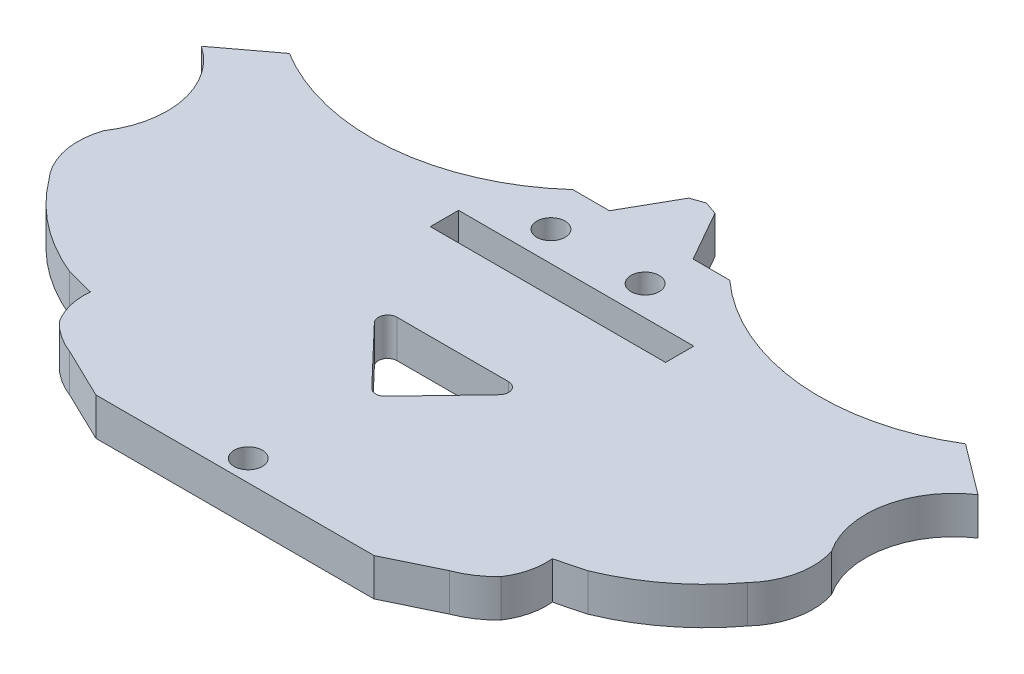
SolidWorks part; units mm, degrees
ref_plane "Front Plane" through (0, 0, 0) normal (0, 0, 1) x (1, 0, 0)
ref_plane "Top Plane" through (0, 0, 0) normal (0, 1, 0) x (1, 0, 0)
ref_plane "Right Plane" through (0, 0, 0) normal (1, 0, 0) x (0, 0, -1)
sketch "Sketch3" plane through (0, 0, 0) normal (0, 1, 0) x (1, 0, 0)
  line L0 (84.4541, 599.5572) -> (574.4541, 599.5572) construction
sketch "Sketch2" plane through (0, 0, 0) normal (0, 1, 0) x (1, 0, 0)
  line L0 (0, 0) -> (0, 57.603) construction
  line L1 (-18.1438, -7.9279) -> (18.1438, -7.9279) construction
  line L2 (-18.1438, -7.9279) -> (-18.1438, 7.9279) construction
  line L3 (-18.1438, 7.9279) -> (18.1438, 7.9279) construction
  line L4 (18.1438, -7.9279) -> (18.1438, 7.9279) construction
  line L5 (-18.1438, -7.9279) -> (18.1438, 7.9279) construction
  line L6 (-18.1438, 7.9279) -> (18.1438, -7.9279) construction
  line L7 (-21.8576, -11.143) -> (21.8576, -11.143) construction
  line L8 (-21.8576, -11.143) -> (-21.8576, 11.143) construction
  line L9 (-21.8576, 11.143) -> (21.8576, 11.143) construction
  line L10 (21.8576, -11.143) -> (21.8576, 11.143) construction
  line L11 (-21.8576, -11.143) -> (21.8576, 11.143) construction
  line L12 (-21.8576, 11.143) -> (21.8576, -11.143) construction
  line L13 (-8.5, 0) -> (8.5, 0) construction
  line L14 (0, 0) -> (0, -8.8619) construction
  line L15 (-20.6395, 7.1502) -> (-17.9674, 9.1598)
  line L16 (-4.1695, 10.4244) -> (4.1695, 10.4244)
  line L17 (-1.5343, -5.6375) -> (1.5343, -5.6375)
  line L18 (-10.0901, -10.3942) -> (-7.3916, -11.6987)
  line L19 (20.6395, 7.1502) -> (17.9674, 9.1598)
  line L20 (-2.2241, 10.4244) -> (-0.6961, 13.1148)
  line L21 (-0.6961, 13.1148) -> (0, 13.358)
  line L22 (2.2241, 10.4244) -> (0.6961, 13.1148)
  line L23 (0.6961, 13.1148) -> (0, 13.358)
  line L24 (-7.3916, -11.6987) -> (-0.7757, -11.143)
  line L25 (-0.7757, -11.143) -> (0, -10.9595)
  line L26 (0.7757, -11.143) -> (0, -10.9595)
  line L27 (7.3916, -11.6987) -> (0.7757, -11.143)
  line L28 (10.0901, -10.3942) -> (7.3916, -11.6987)
  line L29 (-16.4215, -5.191) -> (-11.7373, -9.2961)
  line L30 (16.4215, -5.191) -> (11.7373, -9.2961)
  line L31 (-7.3916, -11.6987) -> (7.3916, -11.6987)
  line L33 (-32.5, -20.0045) -> (32.5, -20.0045)
  line L34 (-32.5, -20.0045) -> (-32.5, 20.0045)
  line L35 (-32.5, 20.0045) -> (32.5, 20.0045)
  line L36 (32.5, -20.0045) -> (32.5, 20.0045)
  line L37 (-32.5, -20.0045) -> (32.5, 20.0045) construction
  line L38 (-32.5, 20.0045) -> (32.5, -20.0045) construction
  arc A0 (-4.1695, 10.4244) -> (-17.9674, 9.1598) centre (-11.9148, 19.0269) cw
  arc A1 (-20.6395, 7.1502) -> (-19.3461, 0.6629) centre (-23.2364, 3.2599) cw
  arc A2 (-19.3461, 0.6629) -> (-18.559, -3.0217) centre (-15.82, -0.5102) ccw
  arc A3 (-18.559, -3.0217) -> (-13.7831, -6.7121) centre (-9.4985, 3.7682) ccw
  arc A4 (-13.7831, -6.7121) -> (-6.6237, -7.9279) centre (-4.6259, 25.5245) ccw
  arc A5 (-1.5343, -5.6375) -> (-6.6237, -7.9279) centre (-1.5343, -12.4372) ccw
  arc A7 (13.7831, -6.7121) -> (6.6237, -7.9279) centre (4.6259, 25.5245) cw
  arc A8 (18.559, -3.0217) -> (13.7831, -6.7121) centre (9.4985, 3.7682) cw
  arc A9 (19.3461, 0.6629) -> (18.559, -3.0217) centre (15.82, -0.5102) cw
  arc A10 (20.6395, 7.1502) -> (19.3461, 0.6629) centre (23.2364, 3.2599) ccw
  arc A11 (4.1695, 10.4244) -> (17.9674, 9.1598) centre (11.9148, 19.0269) ccw
  arc A12 (1.5343, -5.6375) -> (6.6237, -7.9279) centre (1.5343, -12.4372) cw
  arc A14 (-12.2767, -7.1024) -> (-11.7373, -9.2961) centre (-8.8887, -7.4325) ccw
  arc A15 (-11.7373, -9.2961) -> (-10.0901, -10.3942) centre (-8.5052, -6.2323) ccw
  arc A16 (12.2767, -7.1024) -> (11.7373, -9.2961) centre (8.8887, -7.4325) cw
  arc A17 (11.7373, -9.2961) -> (10.0901, -10.3942) centre (8.5052, -6.2323) cw
  point P0 (0, 0)
  point P6 (0, 0)
  point P34 (0, 0)
  point P45 (0, 10.4244)
  point P54 (0, -5.6375)
  point P57 (-0.2087, -5.6375)
  point P72 (0, -11.6987)
  dimension "D2" = 65
  dimension "D1" = 17
extrude "Boss-Extrude1" add sketch "Sketch2" along normal blind 2
sketch "Sketch4" plane through (0, 0, 0) normal (0, 1, 0) x (1, 0, 0)
  line L0 (0, 0) -> (0, -15.9627) construction
  line L1 (0, 0) -> (0, 46.0631) construction
scale "Scale1" bodies to scale 101 scale about centroid uniform scaling yes scale factor 2
sketch "Sketch6" plane through (0, 3, 0) normal (0, 1, 0) x (1, 0, 0)
  line L0 (0, 0) -> (0, 27.4099) construction
  circle A0 centre (-5.8515, 16.2836) radius 1.5 construction
  circle A1 centre (-5.8515, 16.2836) radius 1.5
  circle A2 centre (4.1518, 16.2836) radius 1.5 construction
  circle A3 centre (4.1518, 16.2836) radius 1.5
extrude "Cut-Extrude2" cut sketch "Sketch6" against normal through all
sketch "Sketch7" plane through (0, 3, 0) normal (0, 1, 0) x (1, 0, 0)
  line L0 (0, 0) -> (0, 46.0631) construction
  line L1 (-12.5, 13.1109) -> (12.5, 13.1109)
  line L2 (-12.5, 13.1109) -> (-12.5, 10.1109)
  line L3 (-12.5, 10.1109) -> (12.5, 10.1109)
  line L4 (12.5, 13.1109) -> (12.5, 10.1109)
  line L5 (-12.5, 13.1109) -> (12.5, 10.1109) construction
  line L6 (-12.5, 10.1109) -> (12.5, 13.1109) construction
  point P0 (0, 11.6109)
  dimension "D1" = 3
  dimension "D2" = 25
extrude "Boss-Extrude2" add sketch "Sketch7" along normal blind 15
sketch "Sketch8" plane through (0, 0, -10.1109) normal (0, 0, 1) x (1, 0, 0)
  line L0 (0, 2.6097) -> (0, 7.1828) construction
  line L1 (-8, 16.4174) -> (8, 16.4174)
  line L2 (-8, 16.4174) -> (-8, 5.4174)
  line L3 (-8, 5.4174) -> (8, 5.4174)
  line L4 (8, 16.4174) -> (8, 5.4174)
  circle A0 centre (-9.75, 10.9174) radius 1.5
  circle A1 centre (9.75, 10.9174) radius 1.5
  point P4 (0, 5.4174)
  point P8 (-8, 10.9174)
  dimension "D3" = 3
  dimension "D4" = 1.75
  dimension "D1" = 16
  dimension "D2" = 11
extrude "Cut-Extrude3" cut sketch "Sketch8" against normal blind 18
fillet "Fillet3" radius 3 1 edges at (-12.5, 18, -11.6109)
fillet "Fillet4" radius 3 1 edges at (12.5, 18, -11.6109)
sketch "Sketch9" plane through (0, 3, 0) normal (0, 1, 0) x (1, 0, 0)
  line L21 (-7.6951, -21.8709) -> (-7.6951, -30.6829)
  line L22 (-7.6951, -30.6829) -> (5.9954, -30.6829)
  line L23 (5.9954, -30.6829) -> (5.9954, -21.8709)
  line L24 (5.9954, -21.8709) -> (8.9954, -21.8709)
  line L25 (8.9954, -21.8709) -> (8.9954, -30.0705)
  line L26 (8.9954, -30.0705) -> (18.6231, -24.4632)
  line L27 (18.6231, -24.4632) -> (23.9122, -21.0338)
  line L28 (25.28, -18.5167) -> (25.28, -3.348)
  line L29 (24.6327, -1.4865) -> (9.0527, 18.2043)
  line L30 (6.7, 19.3428) -> (3.3097, 19.3428)
  line L31 (3.3097, 19.3428) -> (0.5459, 24.5621)
  line L32 (0.5459, 24.5621) -> (-0.8499, 25.1844)
  line L33 (-0.8499, 25.1844) -> (-2.2456, 24.5621)
  line L34 (-2.2456, 24.5621) -> (-5.0094, 19.3428)
  line L35 (-5.0094, 19.3428) -> (-8.3997, 19.3428)
  line L36 (-10.7524, 18.2043) -> (-26.3324, -1.4865)
  line L37 (-26.9797, -3.348) -> (-26.9797, -18.5167)
  line L38 (-25.6119, -21.0338) -> (-20.3228, -24.4632)
  line L39 (-20.3228, -24.4632) -> (-10.6951, -30.0705)
  line L40 (-10.6951, -30.0705) -> (-10.6951, -21.8709)
  line L41 (-10.6951, -21.8709) -> (-7.6951, -21.8709)
  line L42 (-7.6951, -21.8709) -> (-7.6951, -30.6829)
  line L43 (-7.6951, -30.6829) -> (5.9954, -30.6829)
  line L44 (5.9954, -30.6829) -> (5.9954, -21.8709)
  line L45 (5.9954, -21.8709) -> (8.9954, -21.8709)
  line L46 (8.9954, -21.8709) -> (8.9954, -30.0705)
  line L47 (8.9954, -30.0705) -> (18.6231, -24.4632)
  line L48 (18.6231, -24.4632) -> (23.9122, -21.0338)
  line L49 (25.28, -18.5167) -> (25.28, -3.348)
  line L50 (24.6327, -1.4865) -> (9.0527, 18.2043)
  line L51 (6.7, 19.3428) -> (3.3097, 19.3428)
  line L52 (3.3097, 19.3428) -> (0.5459, 24.5621)
  line L53 (0.5459, 24.5621) -> (-0.8499, 25.1844)
  line L54 (-0.8499, 25.1844) -> (-2.2456, 24.5621)
  line L55 (-2.2456, 24.5621) -> (-5.0094, 19.3428)
  line L56 (-5.0094, 19.3428) -> (-8.3997, 19.3428)
  line L57 (-10.7524, 18.2043) -> (-26.3324, -1.4865)
  line L58 (-26.9797, -3.348) -> (-26.9797, -18.5167)
  line L59 (-25.6119, -21.0338) -> (-20.3228, -24.4632)
  line L60 (-20.3228, -24.4632) -> (-10.6951, -30.0705)
  line L61 (-10.6951, -30.0705) -> (-10.6951, -21.8709)
  line L62 (-10.6951, -21.8709) -> (-7.6951, -21.8709)
  arc A6 (23.9122, -21.0338) -> (25.28, -18.5167) centre (22.28, -18.5167) ccw
  arc A7 (25.28, -3.348) -> (24.6327, -1.4865) centre (22.28, -3.348) ccw
  arc A8 (9.0527, 18.2043) -> (6.7, 19.3428) centre (6.7, 16.3428) ccw
  arc A9 (-8.3997, 19.3428) -> (-10.7524, 18.2043) centre (-8.3997, 16.3428) ccw
  arc A10 (-26.3324, -1.4865) -> (-26.9797, -3.348) centre (-23.9797, -3.348) ccw
  arc A11 (-26.9797, -18.5167) -> (-25.6119, -21.0338) centre (-23.9797, -18.5167) ccw
  arc A12 (23.9122, -21.0338) -> (25.28, -18.5167) centre (22.28, -18.5167) ccw
  arc A13 (25.28, -3.348) -> (24.6327, -1.4865) centre (22.28, -3.348) ccw
  arc A14 (9.0527, 18.2043) -> (6.7, 19.3428) centre (6.7, 16.3428) ccw
  arc A15 (-8.3997, 19.3428) -> (-10.7524, 18.2043) centre (-8.3997, 16.3428) ccw
  arc A16 (-26.3324, -1.4865) -> (-26.9797, -3.348) centre (-23.9797, -3.348) ccw
  arc A17 (-26.9797, -18.5167) -> (-25.6119, -21.0338) centre (-23.9797, -18.5167) ccw
  dimension "D1" = 0
sketch "Sketch10" plane through (0, 3, 0) normal (0, 1, 0) x (1, 0, 0)
  circle A0 centre (-0.8499, -20.8953) radius 1.5 construction
  circle A1 centre (-0.8499, -20.8953) radius 1.5
extrude "Cut-Extrude4" cut sketch "Sketch10" against normal blind 10
sketch "Sketch11" plane through (0, 3, 0) normal (0, 1, 0) x (1, 0, 0)
  line L1 (-12.5, 13.1109) -> (12.5, 13.1109)
  line L2 (-12.5, 13.1109) -> (-12.5, 10.1109)
  line L3 (-12.5, 10.1109) -> (12.5, 10.1109)
  line L4 (12.5, 13.1109) -> (12.5, 10.1109)
  dimension "D1" = 3
extrude "Cut-Extrude5" cut sketch "Sketch11" against normal through all both and the other way through all
sketch "Sketch12" plane through (0, 3, 0) normal (0, 1, 0) x (1, 0, 0)
  line L0 (-5.9235, 0) -> (5.9235, 0)
  line L1 (6.6466, -1.6907) -> (0.7231, -7.8917)
  line L2 (0, 0) -> (0, -15.9627) construction
  line L3 (0, 10.1109) -> (0, 3.3786) construction
  line L4 (-12.5, 10.1109) -> (12.5, 10.1109) construction
  line L5 (0, 0) -> (0, 46.0631) construction
  line L6 (-6.6466, -1.6907) -> (-0.7231, -7.8917)
  arc A0 (5.9235, 0) -> (6.6466, -1.6907) centre (5.9235, -1) cw
  arc A1 (0.7231, -7.8917) -> (-0.7231, -7.8917) centre (0, -7.2009) cw
  arc A2 (-6.6466, -1.6907) -> (-5.9235, 0) centre (-5.9235, -1) cw
  point P13 (0, 0)
  point P16 (8.2618, 0)
  point P19 (0, -8.6486)
  point P22 (-8.2618, 0)
  dimension "D1" = 1
extrude "Cut-Extrude6" cut sketch "Sketch12" against normal through all both
